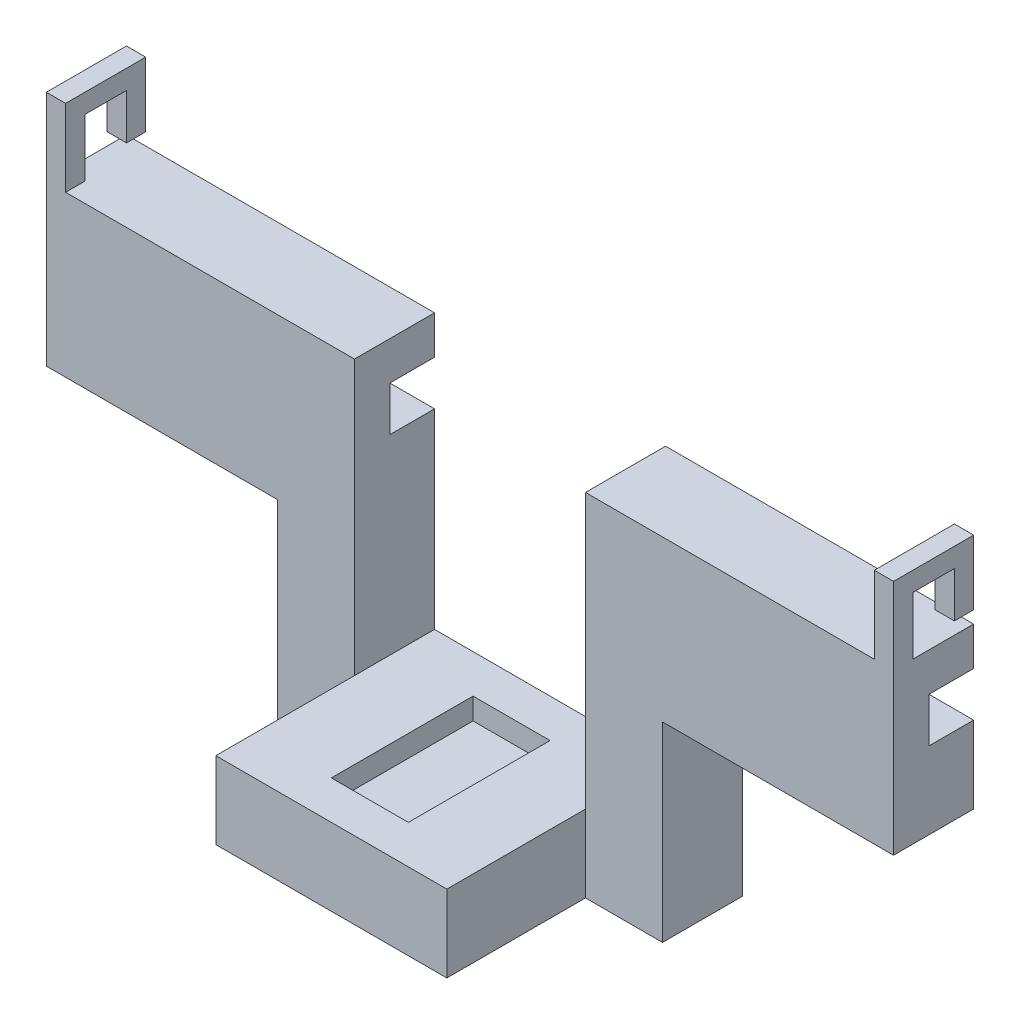
SolidWorks part; units mm, degrees
ref_plane "Front Plane" through (0, 0, 0) normal (0, 0, 1) x (1, 0, 0)
ref_plane "Top Plane" through (0, 0, 0) normal (0, 1, 0) x (1, 0, 0)
ref_plane "Right Plane" through (0, 0, 0) normal (1, 0, 0) x (0, 0, -1)
sketch "Sketch1" plane through (0, 0, 0) normal (0, 0, 1) x (1, 0, 0)
  line L1 (0, 0) -> (139.7, 0)
  line L2 (0, 0) -> (0, 66.04)
  line L3 (0, 66.04) -> (139.7, 66.04)
  line L4 (139.7, 0) -> (139.7, 66.04)
  dimension "D1" = 139.7
  dimension "D2" = 66.04
extrude "Boss-Extrude1" add sketch "Sketch1" along normal blind 13.208 contours L3 L4 L1 L2
sketch "Sketch2" plane through (0, 0, 13.208) normal (0, 0, 1) x (1, 0, 0)
  line L0 (0, 66.04) -> (139.7, 66.04) construction
  line L1 (50.8, 66.04) -> (88.9, 66.04)
  line L2 (50.8, 66.04) -> (50.8, 12.7)
  line L3 (50.8, 12.7) -> (88.9, 12.7)
  line L4 (88.9, 66.04) -> (88.9, 12.7)
  line L5 (0, 0) -> (0, 66.04) construction
  line L6 (0, 0) -> (139.7, 0) construction
  dimension "D1" = 50.8
  dimension "D2" = 12.7
  dimension "D3" = 38.1
extrude "Cut-Extrude1" cut sketch "Sketch2" against normal blind 13.208
sketch "Sketch3" plane through (0, 0, 13.208) normal (0, 0, 1) x (1, 0, 0)
  line L0 (0, 0) -> (139.7, 0) construction
  line L1 (50.8, 12.7) -> (88.9, 12.7)
  line L2 (50.8, 12.7) -> (50.8, 0)
  line L3 (50.8, 0) -> (88.9, 0)
  line L4 (88.9, 12.7) -> (88.9, 0)
extrude "Boss-Extrude2" add sketch "Sketch3" along normal blind 31.242
sketch "Sketch4" plane through (0, 12.7, 0) normal (0, 1, 0) x (1, 0, 0)
  line L0 (50.8, 0) -> (88.9, 0) construction
  line L1 (63.5, -6.35) -> (76.2, -6.35)
  line L2 (63.5, -6.35) -> (63.5, -29.718)
  line L3 (63.5, -29.718) -> (76.2, -29.718)
  line L4 (76.2, -6.35) -> (76.2, -29.718)
  line L5 (50.8, -44.45) -> (50.8, -13.208) construction
  dimension "D1" = 23.368
  dimension "D2" = 12.7
  dimension "D3" = 6.35
  dimension "D4" = 12.7
extrude "Cut-Extrude2" cut sketch "Sketch4" against normal blind 3.556
sketch "Sketch5" plane through (0, 0, 0) normal (0, -1, 0) x (1, 0, 0)
  line L0 (78.359, 22.606) -> (78.359, 0)
  line L1 (78.359, 22.606) -> (61.341, 22.606)
  line L2 (61.341, 22.606) -> (61.341, 0)
  line L3 (78.359, 0) -> (61.341, 0)
  line L4 (72.009, 6.35) -> (72.009, 16.764)
  line L5 (72.009, 6.35) -> (67.691, 6.35)
  line L6 (67.691, 6.35) -> (67.691, 16.764)
  line L7 (72.009, 16.764) -> (67.691, 16.764)
  line L8 (88.9, 44.45) -> (88.9, 13.208) construction
  dimension "D1" = 4.318
  dimension "D2" = 10.414
  dimension "D3" = 5.842
  dimension "D4" = 17.018
  dimension "D5" = 6.35
  dimension "D6" = 6.35
  dimension "D7" = 10.541
extrude "Boss-Extrude3" add sketch "Sketch5" along normal blind 9.525
sketch "Sketch6" plane through (139.7, 0, 0) normal (1, 0, 0) x (0, 0, -1)
  line L0 (0, 0) -> (0, 66.04) construction
  line L1 (0, 51.562) -> (-7.366, 51.562)
  line L2 (0, 51.562) -> (0, 44.196)
  line L3 (0, 44.196) -> (-7.366, 44.196)
  line L4 (-7.366, 51.562) -> (-7.366, 44.196)
  line L5 (-13.208, 0) -> (0, 0) construction
  line L7 (-13.208, 66.04) -> (0, 66.04)
  line L8 (-13.208, 66.04) -> (-13.208, 57.912)
  line L9 (-13.208, 57.912) -> (0, 57.912)
  line L10 (0, 66.04) -> (0, 57.912)
  dimension "D1" = 7.366
  dimension "D2" = 7.366
  dimension "D3" = 44.196
  dimension "D4" = 6.35
extrude "Cut-Extrude3" cut sketch "Sketch6" against normal blind 172.847
sketch "Sketch7" plane through (0, 0, 0) normal (-1, 0, 0) x (0, 0, 1)
  line L0 (0, 59.944) -> (0, 70.612)
  line L1 (0, 70.612) -> (13.208, 70.612)
  line L2 (13.208, 59.944) -> (13.208, 70.612)
  line L3 (3.175, 59.944) -> (3.175, 67.437)
  line L4 (3.175, 67.437) -> (10.033, 67.437)
  line L5 (10.033, 59.944) -> (10.033, 67.437)
  line L6 (3.175, 59.944) -> (0, 59.944)
  line L7 (10.033, 59.944) -> (10.033, 57.912)
  line L8 (10.033, 57.912) -> (13.208, 57.912)
  line L9 (13.208, 59.944) -> (13.208, 57.912)
  dimension "D1" = 6.858
  dimension "D2" = 3.175
  dimension "D3" = 13.208
  dimension "D4" = 3.175
extrude "Boss-Extrude4" add sketch "Sketch7" against normal blind 139.7 contours L1 L2 L9 L8 L7 L5 L4 L3 L6 L0
sketch "Sketch8" plane through (0, 0, 13.208) normal (0, 0, 1) x (1, 0, 0)
  line L0 (139.7, 70.612) -> (0, 70.612) construction
  line L1 (136.525, 57.912) -> (3.175, 57.912)
  line L2 (136.525, 57.912) -> (136.525, 70.612)
  line L3 (136.525, 70.612) -> (3.175, 70.612)
  line L4 (3.175, 57.912) -> (3.175, 70.612)
  line L5 (0, 0) -> (0, 70.612) construction
  line L6 (139.7, 0) -> (139.7, 70.612) construction
  dimension "D1" = 3.175
  dimension "D2" = 3.175
extrude "Cut-Extrude4" cut sketch "Sketch8" against normal blind 139.7
sketch "Sketch9" plane through (0, 0, 0) normal (0, 0, -1) x (-1, 0, 0)
  line L0 (-88.9, 12.7) -> (-88.9, 44.196) construction
  line L1 (-139.7, 0) -> (-101.6, 0)
  line L2 (-139.7, 0) -> (-139.7, 31.496)
  line L3 (-139.7, 31.496) -> (-101.6, 31.496)
  line L4 (-101.6, 0) -> (-101.6, 31.496)
  line L5 (0, 0) -> (-38.1, 0)
  line L6 (0, 0) -> (0, 31.496)
  line L7 (0, 31.496) -> (-38.1, 31.496)
  line L8 (-38.1, 0) -> (-38.1, 31.496)
  line L9 (-88.9, 44.196) -> (-139.7, 44.196) construction
  line L10 (0, 44.196) -> (-50.8, 44.196) construction
  line L11 (-50.8, 44.196) -> (-50.8, 12.7) construction
  dimension "D1" = 12.7
  dimension "D2" = 12.7
  dimension "D3" = 12.7
  dimension "D4" = 12.7
extrude "Cut-Extrude5" cut sketch "Sketch9" against normal blind 139.7
sketch "Sketch10" plane through (0, 12.7, 0) normal (0, 1, 0) x (1, 0, 0)
  line L0 (88.9, -44.45) -> (88.9, -13.208) construction
  line L1 (50.8, -44.45) -> (88.9, -44.45)
  line L2 (50.8, -44.45) -> (50.8, -36.068)
  line L3 (50.8, -36.068) -> (88.9, -36.068)
  line L4 (88.9, -44.45) -> (88.9, -36.068)
  line L5 (63.5, -29.718) -> (76.2, -29.718) construction
  dimension "D1" = 6.35
extrude "Cut-Extrude6" cut sketch "Sketch10" against normal blind 139.7
